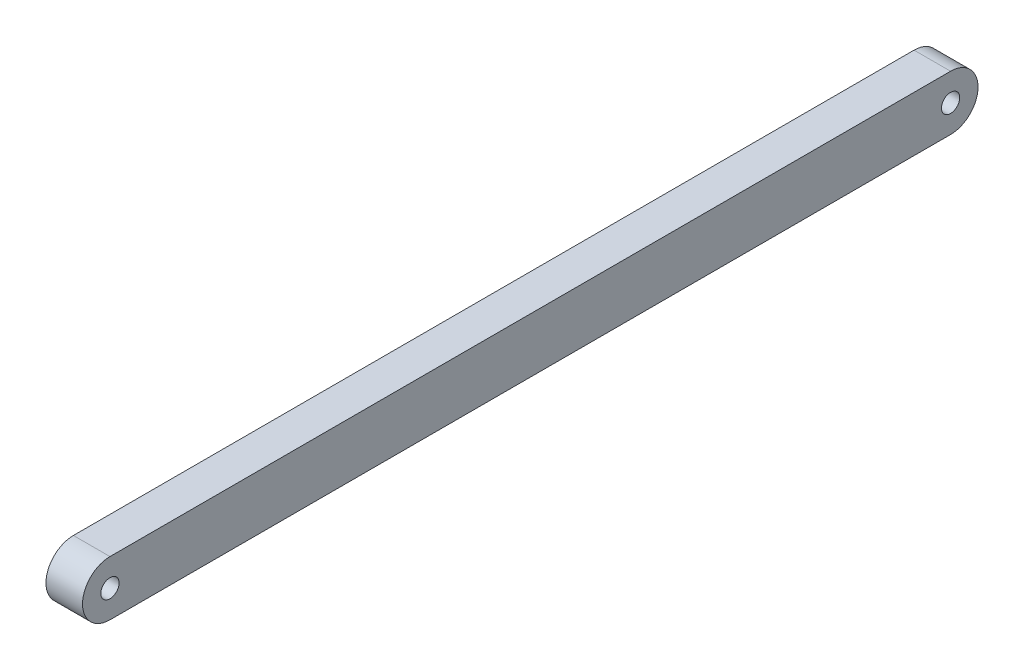
SolidWorks part; units mm, degrees
material "AISI 304"
ref_plane "前视基准面" through (0, 0, 0) normal (0, 0, 1) x (1, 0, 0)
ref_plane "上视基准面" through (0, 0, 0) normal (0, 1, 0) x (1, 0, 0)
ref_plane "右视基准面" through (0, 0, 0) normal (1, 0, 0) x (0, 0, -1)
sketch "草图1" plane through (0, 0, 0) normal (1, 0, 0) x (0, 0, -1)
  line L0 (0, 1.5) -> (46, 1.5)
  line L1 (0, -1.5) -> (46, -1.5)
  circle A0 centre (0, 0) radius 0.5
  arc A1 (0, 1.5) -> (0, -1.5) centre (0, 0) ccw
  circle A2 centre (46, 0) radius 0.5
  arc A3 (46, -1.5) -> (46, 1.5) centre (46, 0) ccw
  dimension "D1" = 3
  dimension "D2" = 1
  dimension "D3" = 46
extrude "凸台-拉伸1" add sketch "草图1" along normal blind 2
